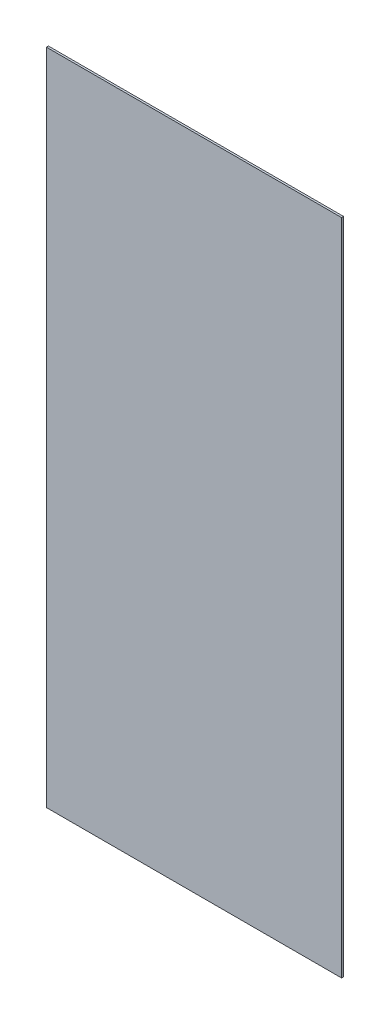
SolidWorks part; units mm, degrees
ref_plane "前视基准面" through (0, 0, 0) normal (0, 0, 1) x (1, 0, 0)
ref_plane "上视基准面" through (0, 0, 0) normal (0, 1, 0) x (1, 0, 0)
ref_plane "右视基准面" through (0, 0, 0) normal (1, 0, 0) x (0, 0, -1)
sketch "草图1" plane through (0, 0, 0) normal (0, 0, 1) x (1, 0, 0)
  line L1 (37.25, -83.1) -> (-37.25, -83.1)
  line L2 (37.25, -83.1) -> (37.25, 83.1)
  line L3 (37.25, 83.1) -> (-37.25, 83.1)
  line L4 (-37.25, -83.1) -> (-37.25, 83.1)
  line L5 (37.25, -83.1) -> (-37.25, 83.1) construction
  line L6 (37.25, 83.1) -> (-37.25, -83.1) construction
  point P0 (0, 0)
  dimension "D1" = 166.2
  dimension "D2" = 74.5
extrude "凸台-拉伸1" add sketch "草图1" along normal mid plane 0.5
